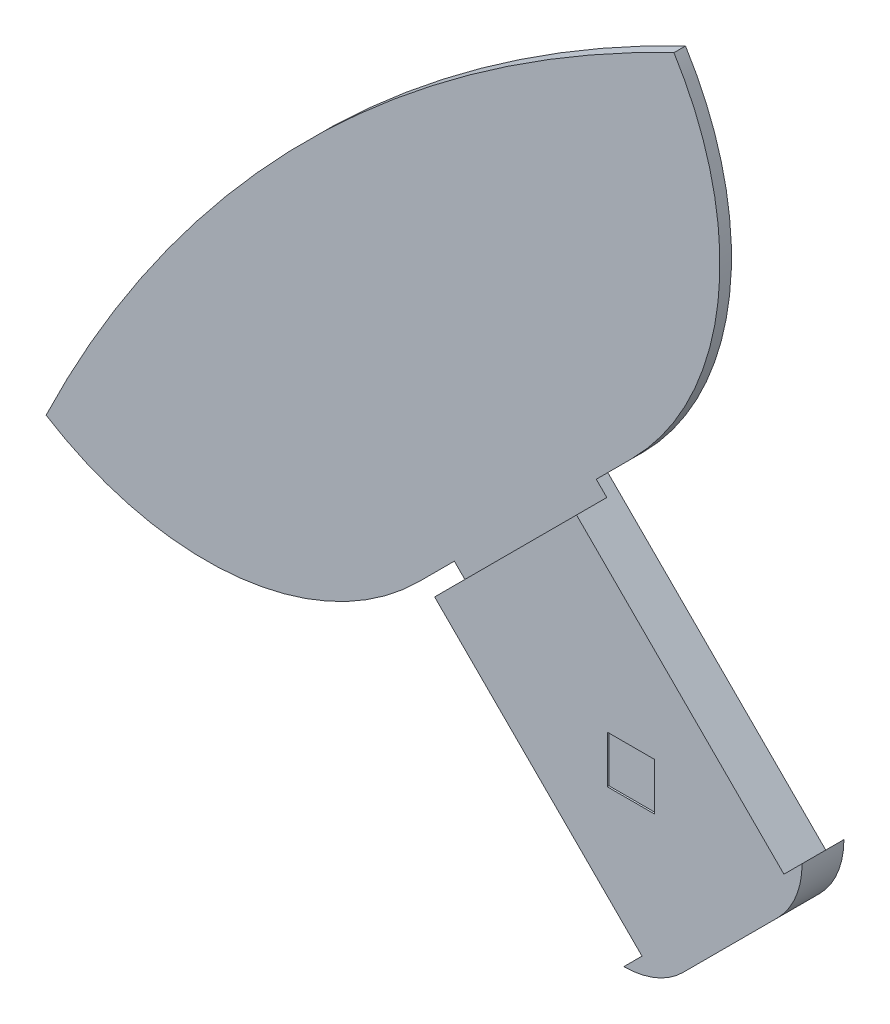
SolidWorks part; units mm, degrees
ref_plane "Front Plane" through (0, 0, 0) normal (0, 0, 1) x (1, 0, 0)
ref_plane "Top Plane" through (0, 0, 0) normal (0, 1, 0) x (1, 0, 0)
ref_plane "Right Plane" through (0, 0, 0) normal (1, 0, 0) x (0, 0, -1)
sketch "Sketch1" plane through (0, 0, 0) normal (0, 0, 1) x (1, 0, 0)
  line L0 (0, 80) -> (0, -80) construction
  line L1 (-80, 0) -> (80, 0) construction
  line L2 (9, -46.6) -> (9, -79.4921)
  line L3 (-4, 41.6) -> (4, 41.6)
  line L4 (-9, 46.6) -> (-9, 79.4921)
  line L6 (9, 46.6) -> (9, 79.4921)
  line L7 (-4, -41.6) -> (4, -41.6)
  line L8 (-9, -46.6) -> (-9, -79.4921)
  line L9 (41.6, 4) -> (41.6, -4)
  line L10 (46.6, -9) -> (79.4921, -9)
  line L11 (46.6, 9) -> (79.4921, 9)
  line L12 (-46.6, -9) -> (-79.4921, -9)
  line L13 (-41.6, 4) -> (-41.6, -4)
  line L14 (-46.6, 9) -> (-79.4921, 9)
  line L15 (26.5872, 32.2441) -> (32.2441, 26.5872)
  line L16 (39.3151, 26.5872) -> (62.5734, 49.8455)
  line L17 (26.5872, 39.3151) -> (49.8455, 62.5734)
  line L18 (-26.5872, 39.3151) -> (-49.8455, 62.5734)
  line L19 (-26.5872, 32.2441) -> (-32.2441, 26.5872)
  line L20 (-39.3151, 26.5872) -> (-62.5734, 49.8455)
  line L21 (0, 0) -> (56.5685, 56.5685) construction
  line L22 (0, 0) -> (-56.5685, 56.5685) construction
  line L23 (-26.5872, -39.3151) -> (-49.8455, -62.5734)
  line L24 (-26.5872, -32.2441) -> (-32.2441, -26.5872)
  line L25 (-39.3151, -26.5872) -> (-62.5734, -49.8455)
  line L26 (26.5872, -39.3151) -> (49.8455, -62.5734)
  line L27 (26.5872, -32.2441) -> (32.2441, -26.5872)
  line L28 (39.3151, -26.5872) -> (62.5734, -49.8455)
  line L29 (-37.1175, 49.8455) -> (-49.8455, 37.1175)
  line L30 (-35.7796, 25.1227) -> (-25.1227, 35.7796)
  line L31 (-47.7241, 39.2389) -> (-34.6938, 26.2085)
  line L32 (-39.2389, 47.7241) -> (-26.2085, 34.6938)
  circle A0 centre (0, 0) radius 80
  arc A1 (41.6, 4) -> (46.6, 9) centre (46.6, 4) cw
  arc A2 (41.6, -4) -> (46.6, -9) centre (46.6, -4) ccw
  arc A3 (32.2441, -26.5872) -> (39.3151, -26.5872) centre (35.7796, -30.1227) cw
  arc A4 (26.5872, -32.2441) -> (26.5872, -39.3151) centre (30.1227, -35.7796) ccw
  arc A5 (4, -41.6) -> (9, -46.6) centre (4, -46.6) cw
  arc A6 (-4, -41.6) -> (-9, -46.6) centre (-4, -46.6) ccw
  arc A7 (-26.5872, -32.2441) -> (-26.5872, -39.3151) centre (-30.1227, -35.7796) cw
  arc A8 (-32.2441, -26.5872) -> (-39.3151, -26.5872) centre (-35.7796, -30.1227) ccw
  arc A9 (-46.6, -9) -> (-41.6, -4) centre (-46.6, -4) ccw
  arc A10 (-41.6, 4) -> (-46.6, 9) centre (-46.6, 4) ccw
  arc A11 (-26.5872, 39.3151) -> (-26.5872, 32.2441) centre (-30.1227, 35.7796) cw
  arc A12 (-32.2441, 26.5872) -> (-39.3151, 26.5872) centre (-35.7796, 30.1227) cw
  arc A13 (-4, 41.6) -> (-9, 46.6) centre (-4, 46.6) cw
  arc A14 (4, 41.6) -> (9, 46.6) centre (4, 46.6) ccw
  arc A15 (32.2441, 26.5872) -> (39.3151, 26.5872) centre (35.7796, 30.1227) ccw
  arc A16 (26.5872, 32.2441) -> (26.5872, 39.3151) centre (30.1227, 35.7796) cw
  arc A17 (34.5941, 72.1335) -> (37.1175, 49.8455) centre (49.8455, 62.5734) ccw
  arc A18 (49.8455, 37.1175) -> (72.1335, 34.5941) centre (62.5734, 49.8455) ccw
  arc A19 (-34.5941, 72.1335) -> (-37.1175, 49.8455) centre (-49.8455, 62.5734) cw
  arc A20 (-49.8455, 37.1175) -> (-72.1335, 34.5941) centre (-62.5734, 49.8455) cw
  arc A21 (-49.8455, -37.1175) -> (-72.1335, -34.5941) centre (-62.5734, -49.8455) ccw
  arc A22 (-34.5941, -72.1335) -> (-37.1175, -49.8455) centre (-49.8455, -62.5734) ccw
  arc A23 (34.5941, -72.1335) -> (37.1175, -49.8455) centre (49.8455, -62.5734) cw
  arc A24 (49.8455, -37.1175) -> (72.1335, -34.5941) centre (62.5734, -49.8455) cw
  arc A25 (-26.5444, 75.4678) -> (-9, 61.4921) centre (-9, 79.4921) ccw
  arc A26 (9, 61.4921) -> (26.5444, 75.4678) centre (9, 79.4921) ccw
  arc A27 (-26.5444, -75.4678) -> (-9, -61.4921) centre (-9, -79.4921) cw
  arc A28 (9, -61.4921) -> (26.5444, -75.4678) centre (9, -79.4921) cw
  arc A29 (-61.4921, 9) -> (-75.4678, 26.5444) centre (-79.4921, 9) ccw
  arc A30 (-75.4678, -26.5444) -> (-61.4921, -9) centre (-79.4921, -9) ccw
  arc A31 (61.4921, 9) -> (75.4678, 26.5444) centre (79.4921, 9) cw
  arc A32 (75.4678, -26.5444) -> (61.4921, -9) centre (79.4921, -9) cw
  circle A33 centre (0, 0) radius 11
  point P44 (41.6, 9)
  point P47 (41.6, -9)
  point P50 (35.7796, -23.0517)
  point P53 (23.0517, -35.7796)
  point P56 (9, -41.6)
  point P59 (-9, -41.6)
  point P62 (-23.0517, -35.7796)
  point P65 (-35.7796, -23.0517)
  point P68 (-41.6, -9)
  point P71 (-41.6, 9)
  point P74 (-23.0517, 35.7796)
  point P77 (-35.7796, 23.0517)
  point P80 (-9, 41.6)
  point P83 (9, 41.6)
  point P86 (35.7796, 23.0517)
  point P89 (23.0517, 35.7796)
  dimension "D1" = 160
  dimension "D13" = 5
  dimension "D14" = 18
  dimension "D15" = 18
  dimension "D16" = 18
  dimension "D17" = 18
  dimension "D18" = 18
  dimension "D20" = 22
  dimension "D2" = 41.6
  dimension "D3" = 41.6
  dimension "D4" = 41.6
  dimension "D5" = 9
  dimension "D6" = 9
  dimension "D7" = 9
  dimension "D8" = 45
  dimension "D9" = 45
  dimension "D10" = 9
  dimension "D11" = 9
  dimension "D12" = 9
  dimension "D19" = 18
  dimension "D21" = 3
  dimension "D22" = 3
extrude "Boss-Extrude2" add sketch "Sketch1" along normal blind 5 contours L32 L29 L31 L30 | L18 A0 L20 L29 | A19 A0 L18 | A20 L20 A0 | A12 L19 A11 L30
ref_plane "Plane1" through (-57.6999, 57.6999, 0) normal (0.7071, -0.7071, 0) x (-0.7071, -0.7071, 0)
sketch "Sketch3" plane through (-57.6999, 57.6999, 0) normal (0.7071, -0.7071, 0) x (-0.7071, -0.7071, 0)
  line L0 (9, 0) -> (6, 0) construction
  line L1 (6, 0) -> (6, -5) construction
  line L2 (6, -5) -> (9, -5) construction
  line L3 (9, -5) -> (9, 0) construction
  line L4 (26.5444, 0) -> (9, 0)
  line L5 (9, 0) -> (9, -5)
  line L6 (9, -5) -> (26.5444, -5)
  line L7 (26.5444, -5) -> (26.5444, 0)
  line L8 (26.5444, 0) -> (9, 0)
  line L9 (9, 0) -> (9, -5)
  line L10 (9, -5) -> (26.5444, -5)
  line L11 (26.5444, -5) -> (26.5444, 0)
  line L12 (7.5355, 0) -> (4, 0) construction
  line L13 (4, -5) -> (7.5355, -5) construction
  line L14 (7.5355, -5) -> (7.5355, 0) construction
  line L15 (4, 0) -> (-4, 0) construction
  line L16 (-4, -5) -> (4, -5) construction
  line L17 (-4, 0) -> (-7.5355, 0) construction
  line L18 (-7.5355, 0) -> (-7.5355, -5) construction
  line L19 (-7.5355, -5) -> (-4, -5) construction
  line L20 (-6, 0) -> (-9, 0) construction
  line L21 (-9, -5) -> (-6, -5) construction
  line L22 (-6, -5) -> (-6, 0) construction
  line L23 (-9, 0) -> (-26.5444, 0) construction
  line L24 (-26.5444, 0) -> (-26.5444, -5) construction
  line L25 (-26.5444, -5) -> (-9, -5) construction
  line L26 (9, 0) -> (6, 0)
  line L27 (6, 0) -> (6, -5)
  line L28 (6, -5) -> (9, -5)
  line L29 (9, -5) -> (9, 0)
  line L30 (7.5355, 0) -> (4, 0)
  line L31 (4, -5) -> (7.5355, -5)
  line L32 (7.5355, -5) -> (7.5355, 0)
  line L33 (4, 0) -> (-4, 0)
  line L34 (-4, -5) -> (4, -5)
  line L35 (-4, 0) -> (-7.5355, 0)
  line L36 (-7.5355, 0) -> (-7.5355, -5)
  line L37 (-7.5355, -5) -> (-4, -5)
  line L38 (-6, 0) -> (-9, 0)
  line L39 (-9, -5) -> (-6, -5)
  line L40 (-6, -5) -> (-6, 0)
  line L41 (-9, 0) -> (-26.5444, 0)
  line L42 (-26.5444, 0) -> (-26.5444, -5)
  line L43 (-26.5444, -5) -> (-9, -5)
  line L45 (26.5444, -3.55) -> (-26.5444, -3.55)
  line L46 (26.5444, -3.55) -> (26.5444, -1.45)
  line L47 (26.5444, -1.45) -> (-26.5444, -1.45)
  line L48 (-26.5444, -3.55) -> (-26.5444, -1.45)
  dimension "D1" = 0
  dimension "D2" = 1.45
  dimension "D3" = 1.45
extrude "Cut-Extrude1" cut sketch "Sketch3" along normal blind 16 from offset 5 contours L36 L47 L42 L45 | L27 L47 L40 L45 | L40 L47 L36 L45 | L32 L47 L27 L45 | L29 L47 L32 L45 | L11 L47 L29 L45
sketch "Sketch4" plane through (-57.6999, 57.6999, 0) normal (0.7071, -0.7071, 0) x (-0.7071, -0.7071, 0)
  line L0 (-7.5355, -5) -> (-7.5355, 0) construction
  line L1 (-7.5355, -5) -> (-7.5355, 0)
  line L2 (-7.5355, -2.5) -> (27.0542, -2.5)
  line L3 (27.0542, -2.5) -> (27.0542, -6.9729)
  line L4 (27.0542, -6.9729) -> (-28.0745, -6.9729)
  line L5 (-28.0745, -6.9729) -> (-28.0745, -2.5)
  line L6 (-28.0745, -2.5) -> (-7.5355, -2.5)
extrude "Cut-Extrude2" cut sketch "Sketch4" along normal blind 52
sketch "Sketch5" plane through (-54.1644, 54.1644, 0) normal (0.7071, -0.7071, 0) x (0, 0, -1)
  line L0 (-2.5, -23.0747) -> (-2.5, 23.0747) construction
  line L1 (-2.5, -23.0747) -> (-1.45, -23.0747) construction
  line L2 (-1.45, -23.0747) -> (-1.45, 23.0747) construction
  line L3 (-1.45, 23.0747) -> (-2.5, 23.0747) construction
  line L4 (-2.5, -23.0747) -> (-2.5, 23.0747)
  line L5 (-2.5, -23.0747) -> (-1.45, -23.0747)
  line L6 (-1.45, -23.0747) -> (-1.45, 23.0747)
  line L7 (-1.45, 23.0747) -> (-2.5, 23.0747)
extrude "Cut-Extrude3" cut sketch "Sketch5" against normal blind 10
sketch "Sketch6" plane through (0, 0, 1.45) normal (0, 0, 1) x (1, 0, 0)
  line L0 (-37.1175, 49.8455) -> (-39.2389, 47.7241) construction
  line L1 (-47.0933, 38.608) -> (-38.608, 47.0933) construction
  line L2 (-39.2389, 47.7241) -> (-38.608, 47.0933) construction
  line L3 (-47.7241, 39.2389) -> (-49.8455, 37.1175) construction
  line L4 (-47.7241, 39.2389) -> (-47.0933, 38.608) construction
  line L5 (-47.7241, 39.2389) -> (-49.8455, 37.1175)
  line L6 (-47.7241, 39.2389) -> (-47.0933, 38.608)
  line L7 (-37.1175, 49.8455) -> (-39.2389, 47.7241)
  line L8 (-39.2389, 47.7241) -> (-38.608, 47.0933)
  line L9 (-47.0933, 38.608) -> (-38.608, 47.0933)
  arc A0 (-34.5941, 72.1335) -> (-72.1335, 34.5941) centre (0, 0) ccw construction
  arc A1 (-72.1335, 34.5941) -> (-49.8455, 37.1175) centre (-62.5734, 49.8455) ccw construction
  arc A2 (-37.1175, 49.8455) -> (-34.5941, 72.1335) centre (-49.8455, 62.5734) ccw construction
  arc A3 (-34.5941, 72.1335) -> (-72.1335, 34.5941) centre (0, 0) ccw
  arc A4 (-72.1335, 34.5941) -> (-49.8455, 37.1175) centre (-62.5734, 49.8455) ccw
  arc A5 (-37.1175, 49.8455) -> (-34.5941, 72.1335) centre (-49.8455, 62.5734) ccw
  point P2 (-38.1782, 48.7848)
extrude "Cut-Extrude4" cut sketch "Sketch6" against normal blind 0.76
sketch "Sketch7" plane through (0, 0, 2.5) normal (0, 0, 1) x (1, 0, 0)
  line L5 (-26.2085, 34.6938) -> (-38.608, 47.0933) construction
  line L6 (-33.9411, 33.9411) -> (-36.7696, 33.9411)
  line L7 (-33.9411, 33.9411) -> (-33.9411, 36.7696)
  line L8 (-33.9411, 36.7696) -> (-36.7696, 36.7696)
  line L9 (-36.7696, 33.9411) -> (-36.7696, 36.7696)
  line L10 (-34.6938, 26.2085) -> (-47.0933, 38.608) construction
  line L11 (-32.2441, 26.5872) -> (-26.5872, 32.2441) construction
  dimension "D1" = 4
  dimension "D2" = 4
  dimension "D3" = 6.4
extrude "Cut-Extrude5" cut sketch "Sketch7" against normal blind 0.1
